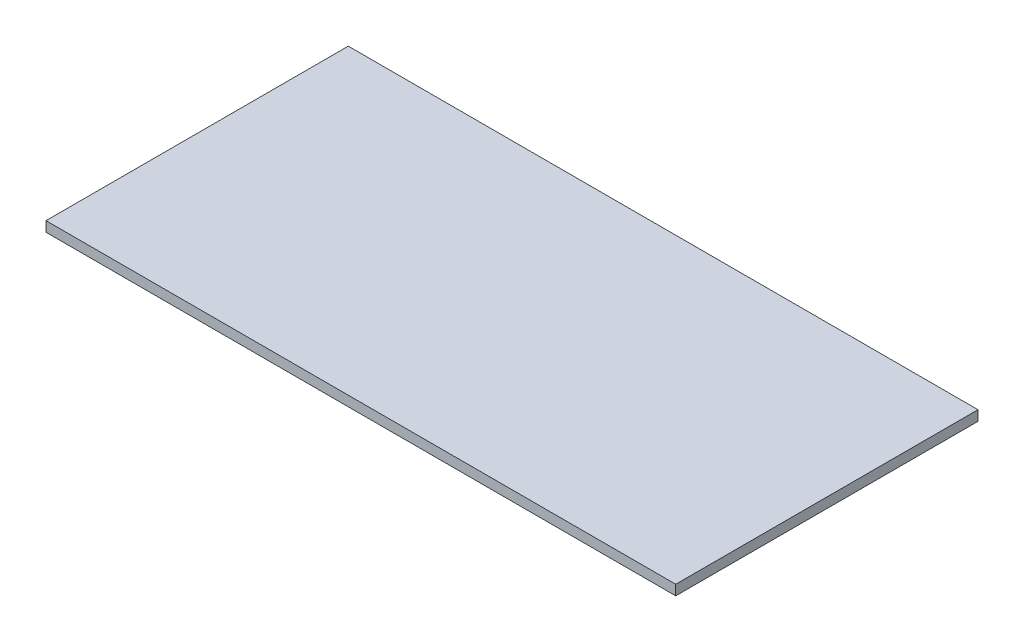
SolidWorks part; units mm, degrees
ref_plane "Front Plane" through (0, 0, 0) normal (0, 0, 1) x (1, 0, 0)
ref_plane "Top Plane" through (0, 0, 0) normal (0, 1, 0) x (1, 0, 0)
ref_plane "Right Plane" through (0, 0, 0) normal (1, 0, 0) x (0, 0, -1)
sketch "Sketch1" plane through (0, 0, 0) normal (0, 1, 0) x (1, 0, 0)
  line L0 (0, 732) -> (0, -742.6667) construction
  line L1 (625, -300) -> (-625, -300)
  line L2 (625, -300) -> (625, 300)
  line L3 (625, 300) -> (-625, 300)
  line L4 (-625, -300) -> (-625, 300)
  line L5 (625, -300) -> (-625, 300) construction
  line L6 (625, 300) -> (-625, -300) construction
  line L7 (-1189.3333, 0) -> (1760, 0) construction
  point P0 (0, 0)
extrude "Boss-Extrude3" add sketch "Sketch1" along normal blind 20
sketch "Sketch6" plane through (0, 0, 0) normal (0, -1, 0) x (1, 0, 0)
  line L0 (768.1275, 0) -> (-1200.5636, 0) construction
  line L1 (565, -250) -> (-565, -250)
  line L2 (565, -250) -> (565, 250)
  line L3 (565, 250) -> (-565, 250)
  line L4 (-565, -250) -> (-565, 250)
  line L5 (565, -250) -> (-565, 250) construction
  line L6 (565, 250) -> (-565, -250) construction
  line L7 (515, -200) -> (-515, -200)
  line L8 (515, -200) -> (515, 200)
  line L9 (515, 200) -> (-515, 200)
  line L10 (-515, -200) -> (-515, 200)
  line L11 (515, -200) -> (-515, 200) construction
  line L12 (515, 200) -> (-515, -200) construction
  point P0 (0, 0)
  point P6 (0, 0)
  dimension "D1" = 500
  dimension "D2" = 1130
  dimension "D3" = 400
  dimension "D4" = 1030
  dimension "D5" = 50
  dimension "D6" = 400
  dimension "D7" = 50
extrude "Cut-Extrude6" cut sketch "Sketch6" against normal blind 1
